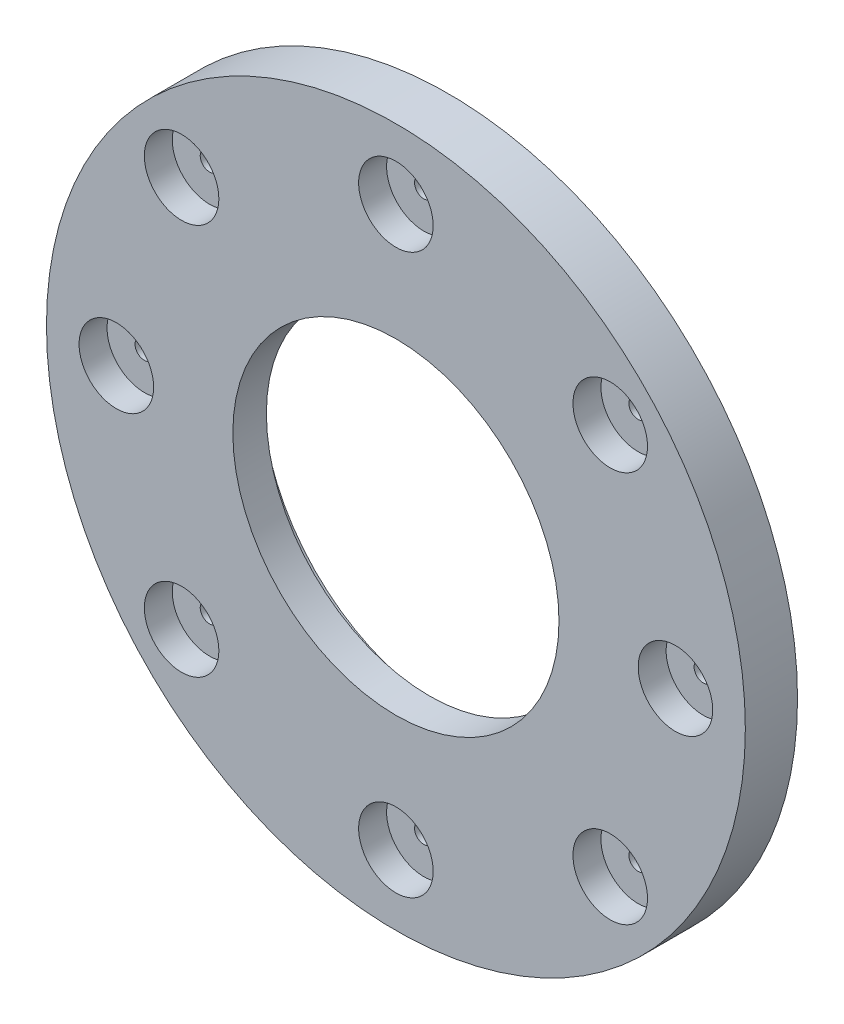
SolidWorks part; units mm, degrees
ref_plane "Спереди" through (0, 0, 0) normal (0, 0, 1) x (1, 0, 0)
ref_plane "Сверху" through (0, 0, 0) normal (0, 1, 0) x (1, 0, 0)
ref_plane "Справа" through (0, 0, 0) normal (1, 0, 0) x (0, 0, -1)
sketch "Эскиз1" plane through (0, 0, 0) normal (0, 0, 1) x (1, 0, 0)
  circle A0 centre (0, 0) radius 37.5
  circle A1 centre (0, 0) radius 20
  circle A2 centre (0, 30) radius 1
  circle A3 centre (0, -30) radius 1
  circle A4 centre (30, 0) radius 1
  circle A5 centre (-30, 0) radius 1
  circle A6 centre (23, 21) radius 1
  circle A7 centre (-23, 21) radius 1
  circle A8 centre (-23, -21) radius 1
  circle A9 centre (23, -21) radius 1
  dimension "D1" = 75
  dimension "D2" = 40
extrude "Бобышка-Вытянуть1" add sketch "Эскиз1" along normal blind 2
sketch "Эскиз2" plane through (0, 0, 2) normal (0, 0, 1) x (1, 0, 0)
  circle A0 centre (0, 0) radius 37.5
  circle A1 centre (0, 0) radius 17.5
  circle A2 centre (0, 30) radius 1
  circle A3 centre (0, -30) radius 1
  circle A4 centre (-30, 0) radius 1
  circle A5 centre (30, 0) radius 1
  circle A6 centre (-23, 21) radius 1
  circle A7 centre (23, 21) radius 1
  circle A8 centre (23, -21) radius 1
  circle A9 centre (-23, -21) radius 1
  dimension "D1" = 75
  dimension "D2" = 35
extrude "Бобышка-Вытянуть2" add sketch "Эскиз2" along normal blind 0.6
sketch "Эскиз3" plane through (0, 0, 2.6) normal (0, 0, 1) x (1, 0, 0)
  circle A0 centre (0, 0) radius 17.5
  circle A1 centre (0, 0) radius 37.5
  circle A2 centre (0, 30) radius 4
  circle A3 centre (0, -30) radius 4
  circle A4 centre (30, 0) radius 4
  circle A5 centre (-30, 0) radius 4
  circle A6 centre (23, 21) radius 4
  circle A7 centre (-23, 21) radius 4
  circle A8 centre (-23, -21) radius 4
  circle A9 centre (23, -21) radius 4
  dimension "D1" = 35
extrude "Бобышка-Вытянуть3" add sketch "Эскиз3" along normal blind 3
